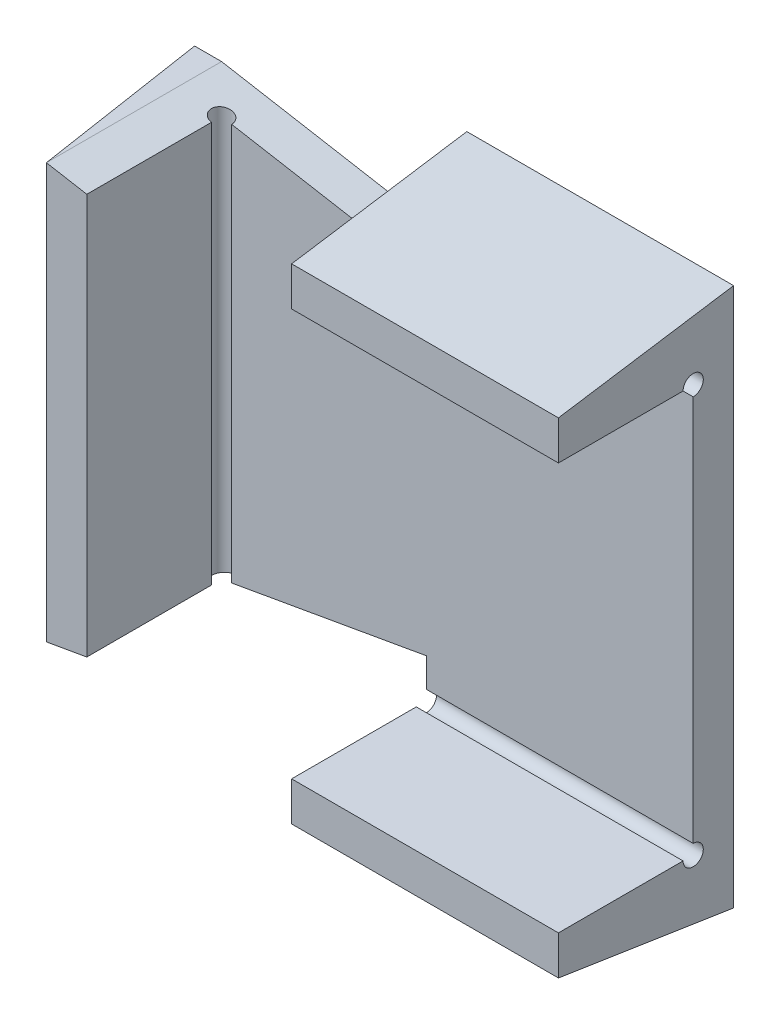
SolidWorks part; units mm, degrees
ref_plane "Plan de face" through (0, 0, 0) normal (0, 0, 1) x (1, 0, 0)
ref_plane "Plan de dessus" through (0, 0, 0) normal (0, 1, 0) x (1, 0, 0)
ref_plane "Plan de droite" through (0, 0, 0) normal (1, 0, 0) x (0, 0, -1)
sketch "Esquisse1" plane through (0, 0, 0) normal (0, 0, 1) x (1, 0, 0)
  line L1 (0, 0) -> (38, 0)
  line L2 (0, 0) -> (0, 36)
  line L3 (0, 36) -> (38, 36)
  line L4 (38, 0) -> (38, 36)
  dimension "D1" = 36
  dimension "D2" = 38
extrude "Boss.-Extru.1" add sketch "Esquisse1" along normal blind 3
sketch "Esquisse2" plane through (0, 0, 3) normal (0, 0, 1) x (1, 0, 0)
  line L0 (0, 18) -> (38, 18) construction
  line L1 (0, 36) -> (0, 0) construction
  line L2 (38, 0) -> (38, 36) construction
  line L3 (38, 33.1) -> (3, 33.1)
  line L4 (3, 33.1) -> (3, 2.9)
  line L5 (0, 0) -> (0, 36)
  line L6 (0, 36) -> (38, 36)
  line L7 (38, 36) -> (38, 33.1)
  line L8 (0, 0) -> (38, 0)
  line L9 (38, 2.9) -> (3, 2.9)
  line L10 (38, 0) -> (38, 2.9)
  point P16 (3, 18)
  dimension "D1" = 30.2
  dimension "D2" = 3
extrude "Boss.-Extru.2" add sketch "Esquisse2" along normal blind 10
sketch "Esquisse3" plane through (0, 0, 0) normal (0, 0, -1) x (-1, 0, 0)
  line L0 (-19, 0) -> (-19, 36) construction
  line L1 (0, 0) -> (-38, 0) construction
  line L2 (-38, 36) -> (0, 36) construction
  line L5 (0, 2.6) -> (0, 0)
  line L8 (0, 2.6) -> (-18.2, 5.8092)
  line L9 (0, 36) -> (0, 0) construction
  line L12 (-3, 2.9) -> (-3, 33.1) construction
  line L13 (0, 0) -> (-18.2, 0)
  line L14 (-18.2, 0) -> (-18.2, 5.8092)
  line L15 (0, 18) -> (-38, 18) construction
  line L16 (-38, 0) -> (-38, 36) construction
  line L17 (-18.2, 36) -> (-18.2, 30.1908)
  line L18 (0, 36) -> (-18.2, 36)
  line L19 (0, 33.4) -> (-18.2, 30.1908)
  line L20 (0, 33.4) -> (0, 36)
  point P16 (-3, 2.9)
  point P25 (-3, 33.1)
  point P26 (0, 0)
  dimension "D1" = 10
  dimension "D2" = 15.2
  dimension "D3" = 2.6
extrude "Enlèv. mat.-Extru.1" cut sketch "Esquisse3" against normal through all both and the other way through all
sketch "Esquisse4" plane through (38, 0, 0) normal (1, 0, 0) x (0, 0, -1)
  circle A0 centre (-3, 2.9) radius 0.75
  circle A1 centre (-3, 33.1) radius 0.75
  dimension "D1" = 1.5
extrude "Enlèv. mat.-Extru.2" cut sketch "Esquisse4" against normal up to surface (19.8 mm away) up to face at (18.2, 33.0969, 5.3333)
sketch "Esquisse5" plane through (0, 0, 0) normal (0, -1, 0) x (1, 0, 0)
  circle A0 centre (3, 3) radius 0.75
  dimension "D1" = 1.5
extrude "Enlèv. mat.-Extru.3" cut sketch "Esquisse5" against normal through all both and the other way through all
sketch "Esquisse6" plane through (0, 0, 0) normal (0, -1, 0) x (1, 0, 0)
  line L0 (0, 0) -> (0, 13)
  line L1 (0, 13) -> (-2, 0)
  line L2 (-2, 0) -> (0, 0)
  dimension "D1" = 2
extrude "Boss.-Extru.3" add sketch "Esquisse6" against normal up to vertex (33.4 mm away) from vertex at -2.6
sketch "Esquisse7" plane through (38, 0, 0) normal (1, 0, 0) x (0, 0, -1)
  line L0 (0, 0) -> (-13, 0)
  line L1 (-13, 0) -> (0, -2)
  line L2 (0, -2) -> (0, 0)
  line L3 (0, 18) -> (-17.613, 18) construction
  line L4 (0, 0) -> (0, 36) construction
  line L5 (0, 38) -> (0, 36)
  line L6 (-13, 36) -> (0, 38)
  line L7 (0, 36) -> (-13, 36)
  dimension "D1" = 2
extrude "Boss.-Extru.4" add sketch "Esquisse7" against normal up to vertex
